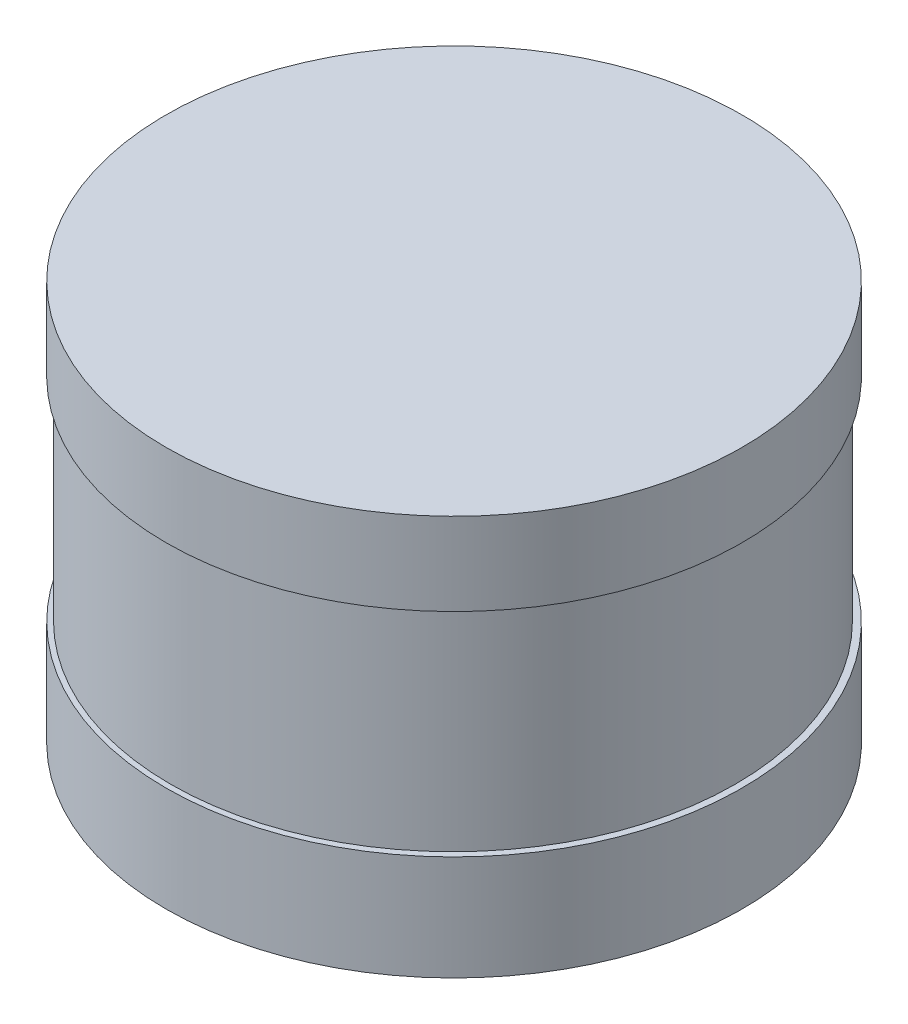
SolidWorks part; units mm, degrees
ref_plane "Front Plane" through (0, 0, 0) normal (0, 0, 1) x (1, 0, 0)
ref_plane "Top Plane" through (0, 0, 0) normal (0, 1, 0) x (1, 0, 0)
ref_plane "Right Plane" through (0, 0, 0) normal (1, 0, 0) x (0, 0, -1)
sketch "Sketch1" plane through (0, 0, 0) normal (0, 1, 0) x (1, 0, 0)
  circle A0 centre (0, 0) radius 51.65
  dimension "D1" = 103.3
extrude "Boss-Extrude1" add sketch "Sketch1" along normal blind 18.8
sketch "Sketch2" plane through (0, 18.8, 0) normal (0, 1, 0) x (1, 0, 0)
  circle A0 centre (0, 0) radius 51.65 construction
  circle A2 centre (-0.2, 0) radius 50.65
  dimension "D1" = 0.8
extrude "Boss-Extrude2" add sketch "Sketch2" along normal blind 38.1 separate body
sketch "Sketch3" plane through (0, 56.9, 0) normal (0, 1, 0) x (1, 0, 0)
  circle A1 centre (0, 0) radius 51.65
extrude "Boss-Extrude3" add sketch "Sketch3" along normal blind 14.8 separate body
sketch "Sketch5" plane through (0, 0, 0) normal (0, -1, 0) x (1, 0, 0)
  line L0 (0, -44.45) -> (0, 44.45) construction
  circle A1 centre (0, -44.45) radius 2.032
  circle A2 centre (0, 44.45) radius 2.032
  dimension "D3" = 4.064
  dimension "D2" = 88.9
extrude "Cut-Extrude1" cut sketch "Sketch5" against normal blind 5.5
sketch "Sketch6" plane through (0, 0, 0) normal (0, -1, 0) x (1, 0, 0)
  circle A0 centre (0, 0) radius 3.175
  dimension "D1" = 6.35
extrude "Cut-Extrude2" cut sketch "Sketch6" against normal blind 7.1
sketch "Sketch7" plane through (0, 0, 0) normal (1, 0, 0) x (0, 0, -1)
  line L0 (-240.3456, 102.2004) -> (240.3456, -26.6004) construction
  line L1 (-240.3456, -26.6004) -> (240.3456, 102.2004) construction
  point P4 (0, 37.8)
  point P5 (0, 37.8)
  dimension "D1" = 37.8
  dimension "D2" = 30
